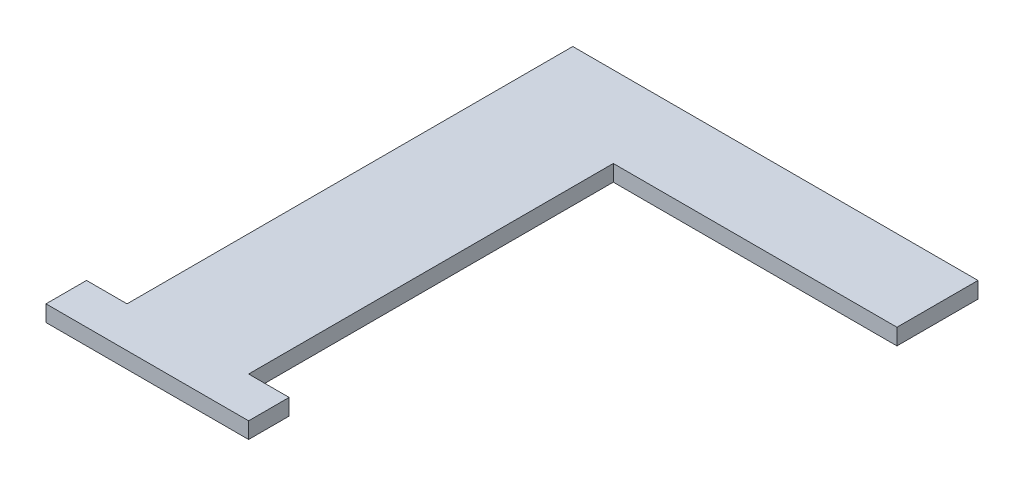
SolidWorks part; units mm, degrees
ref_plane "Front Plane" through (0, 0, 0) normal (0, 0, 1) x (1, 0, 0)
ref_plane "Top Plane" through (0, 0, 0) normal (0, 1, 0) x (1, 0, 0)
ref_plane "Right Plane" through (0, 0, 0) normal (1, 0, 0) x (0, 0, -1)
sketch "Sketch2" plane through (0, 0, 0) normal (0, 1, 0) x (1, 0, 0)
  line L0 (0, 0) -> (-50, 0)
  line L1 (-50, 0) -> (-50, -55)
  line L2 (-50, -60) -> (-35, -60)
  line L3 (-35, -55) -> (-35, -10)
  line L4 (-35, -10) -> (0, -10)
  line L5 (0, -10) -> (0, 0)
  line L6 (-35, -60) -> (-30, -60)
  line L7 (-30, -60) -> (-30, -55)
  line L8 (-30, -55) -> (-35, -55)
  line L9 (-50, -60) -> (-55, -60)
  line L10 (-55, -60) -> (-55, -55)
  line L11 (-55, -55) -> (-50, -55)
  dimension "D1" = 50
  dimension "D2" = 60
  dimension "D3" = 25
  dimension "D4" = 15
  dimension "D5" = 10
  dimension "D6" = 15
  dimension "D7" = 5
  dimension "D8" = 5
  dimension "D9" = 5
extrude "Boss-Extrude1" add sketch "Sketch2" along normal blind 2
